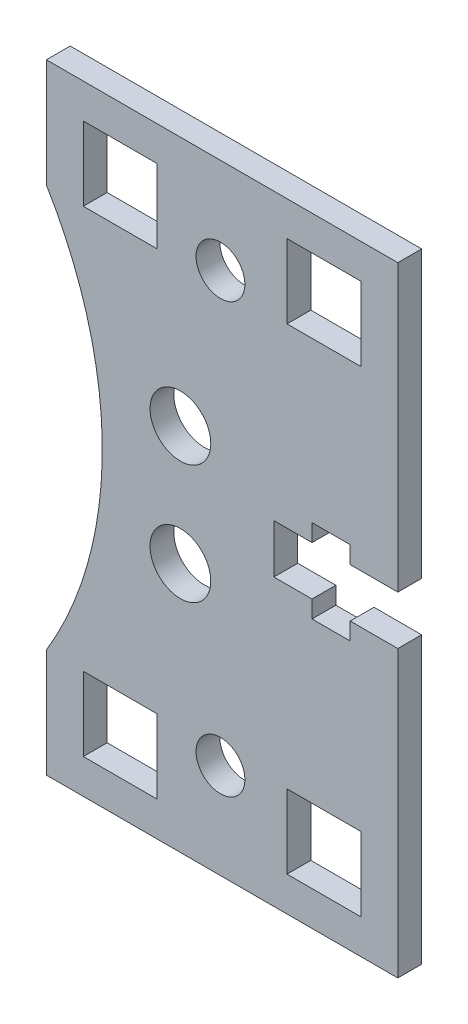
SolidWorks part; units mm, degrees
ref_plane "前视基准面" through (0, 0, 0) normal (0, 0, 1) x (1, 0, 0)
ref_plane "上视基准面" through (0, 0, 0) normal (0, 1, 0) x (1, 0, 0)
ref_plane "右视基准面" through (0, 0, 0) normal (1, 0, 0) x (0, 0, -1)
sketch "草图1" plane through (0, 0, 0) normal (0, 0, 1) x (1, 0, 0)
  line L0 (-10.3431, 0) -> (44.8563, 0) construction
  line L1 (38.2662, -5) -> (38.2662, -19.6678) construction
  line L2 (43.7162, -16.9) -> (43.7162, -23.1)
  line L3 (26.6162, -16.9) -> (32.8162, -16.9)
  line L4 (26.6162, -16.9) -> (26.6162, -23.1)
  line L5 (26.6162, -23.1) -> (32.8162, -23.1)
  line L6 (32.8162, -16.9) -> (32.8162, -23.1)
  line L7 (26.6162, -16.9) -> (32.8162, -23.1) construction
  line L8 (26.6162, -23.1) -> (32.8162, -16.9) construction
  line L9 (49.9162, -23.1) -> (43.7162, -23.1)
  line L10 (49.9162, -16.9) -> (49.9162, -23.1)
  line L11 (49.9162, -16.9) -> (43.7162, -16.9)
  line L12 (32.8162, 16.9) -> (32.8162, 23.1)
  line L13 (26.6162, 23.1) -> (32.8162, 23.1)
  line L14 (26.6162, 16.9) -> (32.8162, 16.9)
  line L15 (26.6162, 16.9) -> (26.6162, 23.1)
  line L16 (43.7162, 16.9) -> (43.7162, 23.1)
  line L17 (49.9162, 23.1) -> (43.7162, 23.1)
  line L18 (49.9162, 16.9) -> (49.9162, 23.1)
  line L19 (49.9162, 16.9) -> (43.7162, 16.9)
  line L20 (43.7162, -16.9) -> (32.8162, 16.9) construction
  line L21 (29.7162, -20) -> (29.7162, -18) construction
  line L22 (53.0162, -26) -> (23.5162, -26)
  line L23 (53.0162, -26) -> (53.0162, 26) construction
  line L24 (53.0162, 26) -> (23.5162, 26)
  line L26 (53.0162, -26) -> (23.5162, 26) construction
  line L27 (53.0162, 26) -> (23.5162, -26) construction
  line L28 (29.7162, -18) -> (46.5434, -18) construction
  line L29 (53.0162, 2.05) -> (49.0162, 2.05)
  line L30 (49.0162, 2.05) -> (49.0162, 3.5)
  line L31 (49.0162, 3.5) -> (45.8162, 3.5)
  line L32 (45.8162, 3.5) -> (45.8162, 2.05)
  line L33 (45.8162, 2.05) -> (42.6162, 2.05)
  line L34 (42.6162, 2.05) -> (42.6162, -2.05)
  line L35 (49.0162, -2.05) -> (49.0162, -3.5)
  line L36 (45.8162, -3.5) -> (45.8162, -2.05)
  line L37 (53.0162, -2.05) -> (49.0162, -2.05)
  line L38 (49.0162, -3.5) -> (45.8162, -3.5)
  line L39 (45.8162, -2.05) -> (42.6162, -2.05)
  line L43 (53.0162, 2.05) -> (53.0162, 26)
  line L47 (53.0162, -26) -> (53.0162, -2.05)
  line L52 (23.5162, 26) -> (23.5162, 16.9)
  line L53 (23.5162, -26) -> (23.5162, -16.9)
  circle A0 centre (34.7662, 5) radius 2.55
  circle A1 centre (38.1298, -18) radius 2.05
  circle A2 centre (34.7662, -5) radius 2.55
  circle A3 centre (38.1298, 18) radius 2.05
  arc A4 (23.5162, 16.9) -> (23.5162, -16.9) centre (-4.5565, 0) cw
  point P8 (29.7162, -20)
  point P10 (38.2662, 0)
  point P19 (46.8162, -20)
  point P28 (46.8162, 20)
  point P55 (42.6162, 0)
  dimension "D2" = 29.5
  dimension "D7" = 52
  dimension "D9" = 4.1
  dimension "D1" = 5
  dimension "D3" = 3.5
  dimension "D4" = 6.2
  dimension "D5" = 6.2
  dimension "D6" = 17.1
  dimension "D8" = 40
  dimension "D10" = 3.2
  dimension "D11" = 4
  dimension "D12" = 3.5
  dimension "D13" = 2.05
extrude "凸台-拉伸1" add sketch "草图1" along normal blind 2
